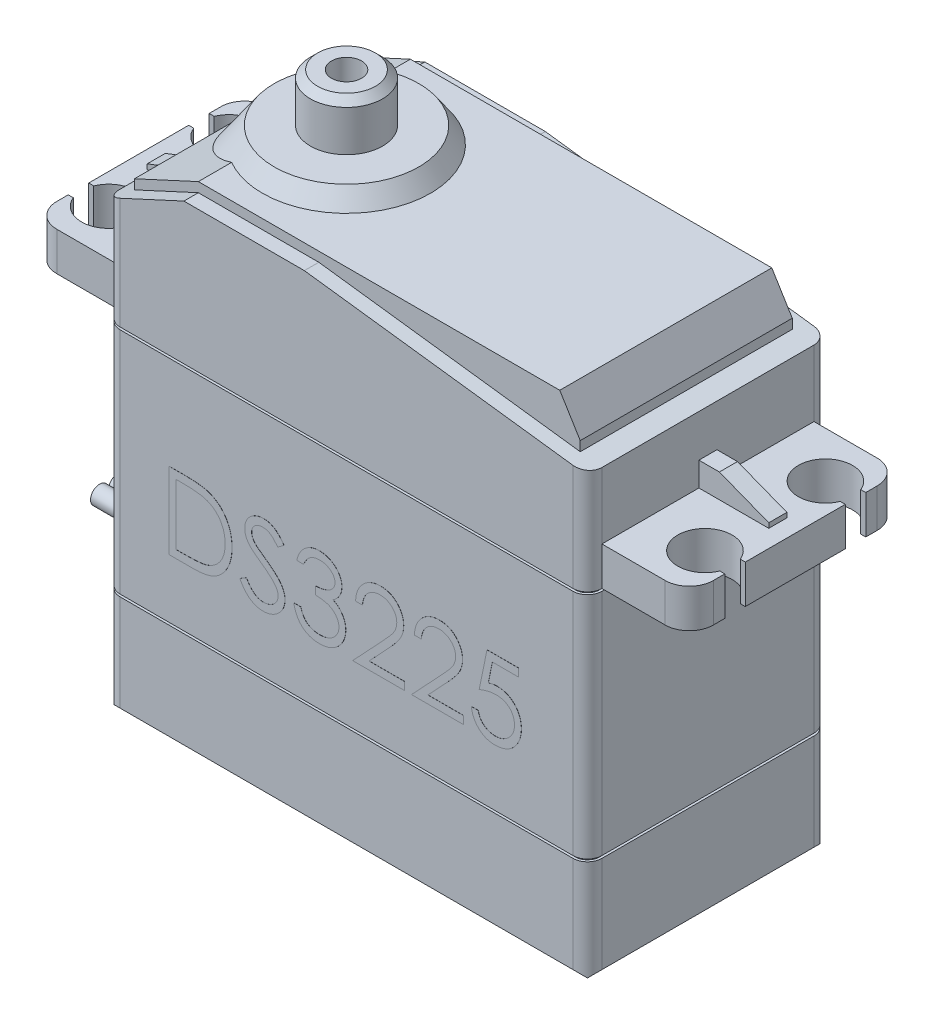
SolidWorks part; units mm, degrees
ref_plane "Front" through (0, 0, 0) normal (0, 0, 1) x (1, 0, 0)
ref_plane "Top" through (0, 0, 0) normal (0, 1, 0) x (1, 0, 0)
ref_plane "Right" through (0, 0, 0) normal (1, 0, 0) x (0, 0, -1)
sketch "Sketch1" plane through (0, 0, 0) normal (0, 1, 0) x (1, 0, 0)
  line L1 (-20, -10) -> (20, -10)
  line L2 (-20, -10) -> (-20, 10)
  line L3 (-20, 10) -> (20, 10)
  line L4 (20, -10) -> (20, 10)
  line L5 (-20, -10) -> (20, 10) construction
  line L6 (-20, 10) -> (20, -10) construction
  point P0 (0, 0)
  dimension "D1" = 20
  dimension "D2" = 40
extrude "Boss-Extrude1" add sketch "Sketch1" along normal blind 41.5
chamfer "Chamfer1" distance 1.6 angle 45 4 edges at (0, 0, -10) (-20, 0, 0) (0, 0, 10) (20, 0, 0)
fillet "Fillet2" radius 1.2 4 edges at (20, 21.55, 10) (20, 21.55, -10) (-20, 21.55, -10) (-20, 21.55, 10)
ref_plane "Plane1" through (0, 29, 0) normal (0, -1, 0) x (-1, 0, 0)
sketch "Sketch3" plane through (0, 29, 0) normal (0, -1, 0) x (-1, 0, 0)
  line L0 (20, 8.8) -> (20, -8.8) construction
  line L1 (-20, -8.8) -> (-20, 8.8) construction
  line L2 (20, 8.8) -> (20, -8.8)
  line L3 (-20, -8.8) -> (-20, 8.8)
  line L4 (-27.25, 5) -> (27.25, 5) construction
  line L5 (-25.25, -8.8) -> (25.25, -8.8)
  line L6 (-27.25, -6.8) -> (-27.25, 6.8)
  line L7 (-25.25, 8.8) -> (25.25, 8.8)
  line L8 (27.25, -6.8) -> (27.25, 6.8)
  line L9 (-27.25, -8.8) -> (27.25, 8.8) construction
  line L10 (-27.25, 8.8) -> (27.25, -8.8) construction
  line L11 (-27.25, 4.15) -> (27.25, 4.15)
  line L12 (-27.25, 5.85) -> (27.25, 5.85)
  line L13 (-27.25, -5) -> (27.25, -5) construction
  line L14 (-27.25, -5.85) -> (27.25, -5.85)
  line L15 (-27.25, -4.15) -> (27.25, -4.15)
  arc A0 (27.25, -6.8) -> (25.25, -8.8) centre (25.25, -6.8) cw
  arc A1 (27.25, 6.8) -> (25.25, 8.8) centre (25.25, 6.8) ccw
  arc A2 (-25.25, -8.8) -> (-27.25, -6.8) centre (-25.25, -6.8) cw
  arc A3 (-25.25, 8.8) -> (-27.25, 6.8) centre (-25.25, 6.8) ccw
  circle A4 centre (-24.75, 5) radius 2.25
  circle A5 centre (24.75, 5) radius 2.25
  circle A6 centre (-24.75, -5) radius 2.25
  circle A7 centre (24.75, -5) radius 2.25
  point P4 (0, 0)
  dimension "D3" = 2
  dimension "D4" = 4.5
  dimension "D5" = 4.5
  dimension "D8" = 4.5
  dimension "D9" = 4.5
  dimension "D1" = 17.6
  dimension "D2" = 54.5
  dimension "D6" = 49.5
  dimension "D7" = 24.75
  dimension "D10" = 10
  dimension "D11" = 5
  dimension "D12" = 0.85
  dimension "D14" = 0.85
  dimension "D13" = 0.85
  dimension "D15" = 0.85
extrude "Boss-Extrude3" add sketch "Sketch3" against normal blind 3.2 contours A5 L12 L8 A1 L7 L2 | A7 L15 L8 L11 A5 L2 | A7 L14 L2 L5 A0 L8 | A7 L15 L2 L14 | A5 L12 L2 L11 | A4 L12 L3 L7 A3 L6 | A4 L11 L3 L12 | A6 L15 L3 L11 A4 L6 | A6 L14 L3 L15 | A6 L14 L6 A2 L5 L3
sketch "Sketch4" plane through (0, 0, 10) normal (0, 0, 1) x (1, 0, 0)
  line L0 (-20, 37.7) -> (-13.5, 40.7)
  line L1 (-20, 32.2) -> (-20, 41.5) construction
  line L2 (-13.5, 40.7) -> (-3.5, 40.7)
  line L3 (-3.5, 40.7) -> (20, 37.7)
  line L4 (20, 41.5) -> (20, 32.2) construction
  line L5 (20, 37.7) -> (20, 41.5)
  line L6 (20, 41.5) -> (-20, 41.5)
  line L7 (-20, 41.5) -> (-20, 37.7)
  dimension "D1" = 3.8
  dimension "D2" = 3.8
  dimension "D3" = 0.8
  dimension "D4" = 10
  dimension "D5" = 6.5
extrude "Cut-Extrude1" cut sketch "Sketch4" against normal up to next
sketch "Sketch5" plane through (0, 0, 0) normal (0, 0, 1) x (1, 0, 0)
  line L0 (-13.5, 41.5) -> (16.5, 41.5)
  line L1 (16.5, 41.5) -> (18.2, 38.7298)
  line L2 (18.2, 38.7298) -> (18.2, 37.9298)
  line L3 (-3.5, 40.7) -> (18.8, 37.8532) construction
  line L4 (18.2, 37.9298) -> (-3.5, 40.7)
  line L5 (-3.5, 40.7) -> (-13.5, 40.7)
  line L6 (-13.5, 40.7) -> (-18.8, 38.2538)
  line L7 (-18.8, 38.2538) -> (-13.5, 40.7) construction
  line L8 (-18.8, 38.2538) -> (-18.8, 39.0538)
  line L9 (-18.8, 39.0538) -> (-13.5, 41.5)
  line L10 (-20, 32.2) -> (-20, 37.7) construction
  line L11 (20, 37.7) -> (20, 32.2) construction
  point P14 (-18.8, 38.6538)
  point P19 (0, 0)
  dimension "D1" = 0.8
  dimension "D2" = 1.2
  dimension "D3" = 1.8
  dimension "D4" = 0.8
  dimension "D5" = 30
extrude "Boss-Extrude4" add sketch "Sketch5" along normal mid plane 17.6
ref_plane "Plane2" through (0, 42.9, 0) normal (0, 1, 0) x (1, 0, 0)
sketch "Sketch6" plane through (0, 42.9, 0) normal (0, 1, 0) x (1, 0, 0)
  line L0 (-27.25, -4.15) -> (-27.25, 4.15) construction
  circle A0 centre (-10, 0) radius 6
  point P2 (0, 0)
  dimension "D1" = 12
  dimension "D2" = 17.25
extrude "Boss-Extrude5" add sketch "Sketch6" against normal up to next draft 35 draft outward yes
sketch "Sketch7" plane through (0, 42.9, 0) normal (0, 1, 0) x (1, 0, 0)
  circle A0 centre (-10, 0) radius 3
  circle A1 centre (-10, 0) radius 1.25
  dimension "D1" = 6
  dimension "D2" = 2.5
extrude "Boss-Extrude6" add sketch "Sketch7" along normal blind 4
chamfer "Chamfer2" distance 0.6 angle 45 1 edges at (-10, 46.9, 3)
sketch "Sketch8" plane through (0, 0, 0) normal (0, 0, 1) x (1, 0, 0)
  line L0 (-20, 34.2) -> (-21.7, 34.2)
  line L1 (-20, 32.2) -> (-20, 37.7) construction
  line L2 (-21.7, 34.2) -> (-25.8, 32.6)
  line L3 (-25.8, 32.6) -> (-25.8, 32.2)
  line L4 (-20, 32.2) -> (-25.25, 32.2) construction
  line L5 (-25.8, 32.2) -> (-20, 32.2)
  line L6 (-20, 32.2) -> (-20, 34.2)
  line L7 (0, 0) -> (0, 11.9728) construction
  line L8 (20, 32.2) -> (20, 34.2)
  line L9 (25.8, 32.2) -> (20, 32.2)
  line L10 (25.8, 32.6) -> (25.8, 32.2)
  line L11 (21.7, 34.2) -> (25.8, 32.6)
  line L12 (20, 34.2) -> (21.7, 34.2)
  dimension "D1" = 5.8
  dimension "D2" = 1.7
  dimension "D3" = 2
  dimension "D4" = 0.4
extrude "Boss-Extrude7" add sketch "Sketch8" along normal mid plane 1.5
ref_plane "Plane3" through (0, 9.6, 0) normal (0, -1, 0) x (-1, 0, 0)
sketch "Sketch9" plane through (0, 9.6, 0) normal (0, -1, 0) x (-1, 0, 0)
  line L0 (20, 8.8) -> (20, -8.8) construction
  line L1 (18.8, -10) -> (-18.8, -10) construction
  line L2 (-20, -8.8) -> (-20, 8.8) construction
  line L3 (-18.8, 10) -> (18.8, 10) construction
  line L4 (20, 8.8) -> (20, -8.8)
  line L5 (18.8, -10) -> (-18.8, -10)
  line L6 (-20, -8.8) -> (-20, 8.8)
  line L7 (-18.8, 10) -> (18.8, 10)
  line L8 (-18.8, 9.8) -> (18.8, 9.8)
  line L9 (19.8, 8.8) -> (19.8, -8.8)
  line L10 (18.8, -9.8) -> (-18.8, -9.8)
  line L11 (-19.8, -8.8) -> (-19.8, 8.8)
  arc A0 (19.6485, 9.6485) -> (18.8, 10) centre (18.8, 8.8) ccw construction
  arc A1 (20, 8.8) -> (19.6485, 9.6485) centre (18.8, 8.8) ccw construction
  arc A2 (19.6485, -9.6485) -> (20, -8.8) centre (18.8, -8.8) ccw construction
  arc A3 (18.8, -10) -> (19.6485, -9.6485) centre (18.8, -8.8) ccw construction
  arc A4 (-19.6485, -9.6485) -> (-18.8, -10) centre (-18.8, -8.8) ccw construction
  arc A5 (-20, -8.8) -> (-19.6485, -9.6485) centre (-18.8, -8.8) ccw construction
  arc A6 (-18.8, 10) -> (-19.6485, 9.6485) centre (-18.8, 8.8) ccw construction
  arc A7 (-19.6485, 9.6485) -> (-20, 8.8) centre (-18.8, 8.8) ccw construction
  arc A8 (19.6485, 9.6485) -> (18.8, 10) centre (18.8, 8.8) ccw
  arc A9 (20, 8.8) -> (19.6485, 9.6485) centre (18.8, 8.8) ccw
  arc A10 (19.6485, -9.6485) -> (20, -8.8) centre (18.8, -8.8) ccw
  arc A11 (18.8, -10) -> (19.6485, -9.6485) centre (18.8, -8.8) ccw
  arc A12 (-19.6485, -9.6485) -> (-18.8, -10) centre (-18.8, -8.8) ccw
  arc A13 (-20, -8.8) -> (-19.6485, -9.6485) centre (-18.8, -8.8) ccw
  arc A14 (-18.8, 10) -> (-19.6485, 9.6485) centre (-18.8, 8.8) ccw
  arc A15 (-19.6485, 9.6485) -> (-20, 8.8) centre (-18.8, 8.8) ccw
  arc A16 (19.5071, 9.5071) -> (18.8, 9.8) centre (18.8, 8.8) ccw
  arc A17 (19.8, 8.8) -> (19.5071, 9.5071) centre (18.8, 8.8) ccw
  arc A18 (19.5071, -9.5071) -> (19.8, -8.8) centre (18.8, -8.8) ccw
  arc A19 (18.8, -9.8) -> (19.5071, -9.5071) centre (18.8, -8.8) ccw
  arc A20 (-19.5071, -9.5071) -> (-18.8, -9.8) centre (-18.8, -8.8) ccw
  arc A21 (-19.8, -8.8) -> (-19.5071, -9.5071) centre (-18.8, -8.8) ccw
  arc A22 (-19.5071, 9.5071) -> (-19.8, 8.8) centre (-18.8, 8.8) ccw
  arc A23 (-18.8, 9.8) -> (-19.5071, 9.5071) centre (-18.8, 8.8) ccw
  dimension "D1" = 0.2
extrude "Cut-Extrude2" cut sketch "Sketch9" against normal blind 0.2
pattern_linear "LPattern1" count 2 spacing 19.2 along (0, 1, 0) of "Cut-Extrude2"
sketch "Sketch10" plane through (-20, 0, 0) normal (-1, 0, 0) x (0, 0, 1)
  line L0 (8.8, 9.6) -> (-8.8, 9.6) construction
  line L1 (-3, 9.6) -> (3, 9.6)
  line L2 (-3.5, 9.1) -> (-3.5, 6.1)
  line L3 (-3, 5.6) -> (3, 5.6)
  line L4 (3.5, 9.1) -> (3.5, 6.1)
  line L5 (-3.5, 9.6) -> (3.5, 5.6) construction
  line L6 (-3.5, 5.6) -> (3.5, 9.6) construction
  arc A0 (-3.5, 6.1) -> (-3, 5.6) centre (-3, 6.1) ccw
  arc A1 (3, 5.6) -> (3.5, 6.1) centre (3, 6.1) ccw
  arc A2 (3, 9.6) -> (3.5, 9.1) centre (3, 9.1) cw
  arc A3 (-3, 9.6) -> (-3.5, 9.1) centre (-3, 9.1) ccw
  point P0 (0, 7.6)
  point P5 (0, 0)
  dimension "D3" = 0.5
  dimension "D1" = 4
  dimension "D2" = 7
extrude "Boss-Extrude8" add sketch "Sketch10" along normal blind 0.6
sketch "Sketch11" plane through (-20.6, 0, 0) normal (-1, 0, 0) x (0, 0, 1)
  line L4 (3.5, 7.6) -> (2.1788, 7.6) construction
  line L5 (-3.2, 5.9) -> (3.2, 5.9)
  line L6 (-3.2, 5.9) -> (-3.2, 9.3)
  line L7 (-3.2, 9.3) -> (3.2, 9.3)
  line L8 (3.2, 5.9) -> (3.2, 9.3)
  line L9 (-3.2, 5.9) -> (3.2, 9.3) construction
  line L10 (-3.2, 9.3) -> (3.2, 5.9) construction
  line L11 (3.5, 6.1) -> (3.5, 9.1) construction
  point P0 (0, 7.6)
  point P9 (0, 5.0749)
  point P10 (0, 0)
  dimension "D1" = 3.4
  dimension "D2" = 6.4
extrude "Boss-Extrude9" add sketch "Sketch11" along normal blind 4.2 draft 5
fillet "Fillet3" radius 0.5 8 edges at (-24.8, 6.2675, 0) (-24.8, 7.6, -2.8325) (-24.8, 8.9325, 0) (-24.8, 7.6, 2.8325) (-22.7, 6.0837, -3.0163) (-22.7, 9.1163, -3.0163) (-22.7, 6.0837, 3.0163) (-22.7, 9.1163, 3.0163)
sketch "Sketch12" plane through (-24.8, 0, 0) normal (-1, 0, 0) x (0, 0, 1)
  line L0 (2.3744, 7.6) -> (-2.3744, 7.6) construction
  line L1 (2.3744, 6.7256) -> (2.3744, 8.4744) construction
  line L2 (-2.3744, 8.4744) -> (-2.3744, 6.7256) construction
  line L3 (0, 8.4744) -> (0, 7.2066) construction
  line L4 (2.3744, 8.4744) -> (-2.3744, 8.4744) construction
  circle A0 centre (-1.5, 7.6) radius 0.75
  circle A1 centre (0, 7.6) radius 0.75
  circle A2 centre (1.5, 7.6) radius 0.75
  point P2 (0, 0)
  point P9 (0, 0)
  dimension "D1" = 1.5
  dimension "D2" = 3
extrude "Boss-Extrude11" add sketch "Sketch12" along normal blind 4.2 separate body contours A0 | A1 | A2
sketch "Sketch13" plane through (0, 0, 10) normal (0, 0, 1) x (1, 0, 0)
  line L0 (-15.52, 14.6807) -> (14.3015, 14.6807) construction
  text T0 "DS3225"
  point P3 (-14.5752, 17.0428)
  point P4 (-14.8704, 16.5113)
  point P5 (-15.52, 18.401)
  point P6 (-13.9256, 9.6613)
  point P7 (-14.5752, 14.7398)
  point P8 (-15.52, 14.6807)
extrude "Boss-Extrude12" add sketch "Sketch13" along normal blind 0.01
